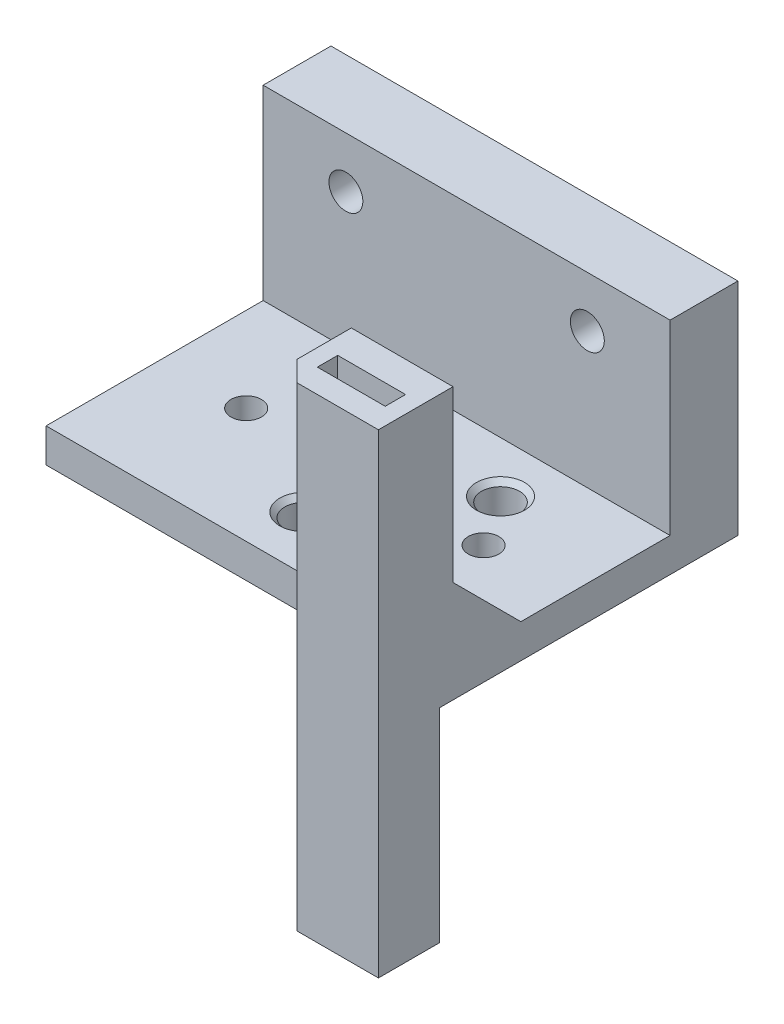
SolidWorks part; units mm, degrees
material "PET"
ref_plane "Front Plane" through (0, 0, 0) normal (0, 0, 1) x (1, 0, 0)
ref_plane "Top Plane" through (0, 0, 0) normal (0, 1, 0) x (1, 0, 0)
ref_plane "Right Plane" through (0, 0, 0) normal (1, 0, 0) x (0, 0, -1)
sketch "Sketch1" plane through (0, 0, 0) normal (0, 1, 0) x (1, 0, 0)
  line L0 (-30, 15) -> (30, 15) construction
  line L2 (-30, 0) -> (-30, 40)
  line L3 (-30, 40) -> (30, 40)
  line L4 (30, 0) -> (30, 40)
  line L5 (0, 0) -> (30, 40) construction
  line L6 (-30, 40) -> (0, 0) construction
  line L7 (-30, 22.5) -> (30, 22.5) construction
  line L8 (-30, 0) -> (-30, -2)
  line L11 (-30, -2) -> (30, -2)
  line L12 (30, -2) -> (30, 0)
  line L13 (-30, 0) -> (30, 0) construction
  line L14 (0, 0) -> (0, 27.8808) construction
  circle A0 centre (-12.5, 22.5) radius 2.8
  circle A1 centre (12.5, 22.5) radius 2.8
  circle A3 centre (-17.5, 15) radius 2.25
  circle A4 centre (17.5, 15) radius 2.25
  circle A6 centre (0, 6) radius 2.8
  point P0 (0, 0)
  dimension "D6" = 5.6
  dimension "D7" = 5.6
  dimension "D8" = 4.5
  dimension "D9" = 4.5
  dimension "D5" = 5.6
  dimension "D2" = 60
  dimension "D4" = 17.5
  dimension "D10" = 12.5
  dimension "D11" = 12.5
  dimension "D12" = 25
  dimension "D17" = 40
  dimension "D18" = 30
  dimension "D20" = 17.5
  dimension "D21" = 17.5
  dimension "D3" = 2
  dimension "D13" = 6
extrude "Boss-Extrude1" add sketch "Sketch1" along normal blind 5
sketch "Sketch3" plane through (0, 5, 0) normal (0, 1, 0) x (1, 0, 0)
  line L2 (-30, 40) -> (-30, 30)
  line L3 (-30, 30) -> (30, 30)
  line L5 (30, 40) -> (-30, 40)
  line L6 (30, 40) -> (30, 30)
  dimension "D2" = 10
extrude "Boss-Extrude3" add sketch "Sketch3" along normal blind 27.5
sketch "Sketch4" plane through (0, 0, -40) normal (0, 0, -1) x (-1, 0, 0)
  line L0 (-30, 0) -> (30, 0) construction
  line L2 (-17.8, 25) -> (17.8, 25) construction
  circle A0 centre (-17.8, 25) radius 2.5
  circle A1 centre (17.8, 25) radius 2.5
  dimension "D3" = 5
  dimension "D4" = 5
  dimension "D1" = 17.8
  dimension "D2" = 35.6
  dimension "D5" = 25
extrude "Cut-Extrude1" cut sketch "Sketch4" against normal through all
chamfer "Chamfer1" distance 0.75 angle 45 3 edges at (-12.5, 5, -19.7) (12.5, 5, -19.7) (0, 5, -3.2)
sketch "Sketch5" plane through (0, 0, 0) normal (0, -1, 0) x (1, 0, 0)
  line L0 (18, 13) -> (15, 10)
  line L1 (30, 2) -> (15, 2)
  line L2 (30, 2) -> (30, 13)
  line L3 (30, 13) -> (18, 13)
  line L6 (15, 2) -> (15, 10)
  line L7 (27.5, 9.5) -> (17.5, 9.5)
  line L8 (27.5, 9.5) -> (27.5, 6.5)
  line L9 (27.5, 6.5) -> (17.5, 6.5)
  line L10 (17.5, 9.5) -> (17.5, 6.5)
  dimension "D1" = 11
  dimension "D2" = 12
  dimension "D3" = 10
  dimension "D4" = 2.5
  dimension "D5" = 3
  dimension "D6" = 4.5
  dimension "D7" = 15
  dimension "D8" = 135
extrude "Boss-Extrude4" add sketch "Sketch5" along normal blind 30 and the other way blind 40
chamfer "Chamfer2" distance 10 angle 45 1 edges at (22.5, 5, 2)
chamfer "Chamfer3" distance 5 angle 45 2 edges at (15, 5, -3) (15, 2.5, 2)
sketch "Sketch7" plane through (30, 0, 0) normal (1, 0, 0) x (0, 0, -1)
  line L0 (-2, -30) -> (-13, -30) construction
  line L1 (-2, 0) -> (-4, 0)
  line L2 (-2, 0) -> (-2, -30)
  line L3 (-2, -30) -> (-4, -30)
  line L4 (-4, 0) -> (-4, -30)
  dimension "D1" = 2
extrude "Cut-Extrude2" cut sketch "Sketch7" against normal through all
sketch "Sketch8" plane through (30, 0, 0) normal (1, 0, 0) x (0, 0, -1)
  line L0 (30, 32.5) -> (-2, 32.5)
  line L2 (-2, 32.5) -> (-2, 15)
  line L3 (-2, 15) -> (8, 5)
  line L4 (8, 5) -> (30, 5)
  line L5 (30, 5) -> (30, 32.5)
extrude "Boss-Extrude5" add sketch "Sketch8" against normal blind 5
sketch "Sketch9" plane through (25, 0, 0) normal (-1, 0, 0) x (0, 0, 1)
  line L0 (-30, 32.5) -> (-30, 5)
  line L1 (-30, 5) -> (-8, 5)
  line L2 (-8, 5) -> (2, 15)
  line L3 (2, 15) -> (2, 32.5)
  line L5 (2, 32.5) -> (-30, 32.5)
extrude "Cut-Extrude3" cut sketch "Sketch9" against normal through all
sketch "Sketch10" plane through (0, 0, -40) normal (0, 0, -1) x (-1, 0, 0)
  line L0 (-17.8, 25) -> (17.8, 25) construction
  circle A0 centre (0, 25) radius 2.5
  dimension "D1" = 5
extrude "Cut-Extrude4" cut sketch "Sketch10" against normal blind 2
equation "\"D18@Sketch1\"=\"D2@Sketch1\"/2"
equation "\"D1@Sketch4\"=\"D2@Sketch4\"/2"
